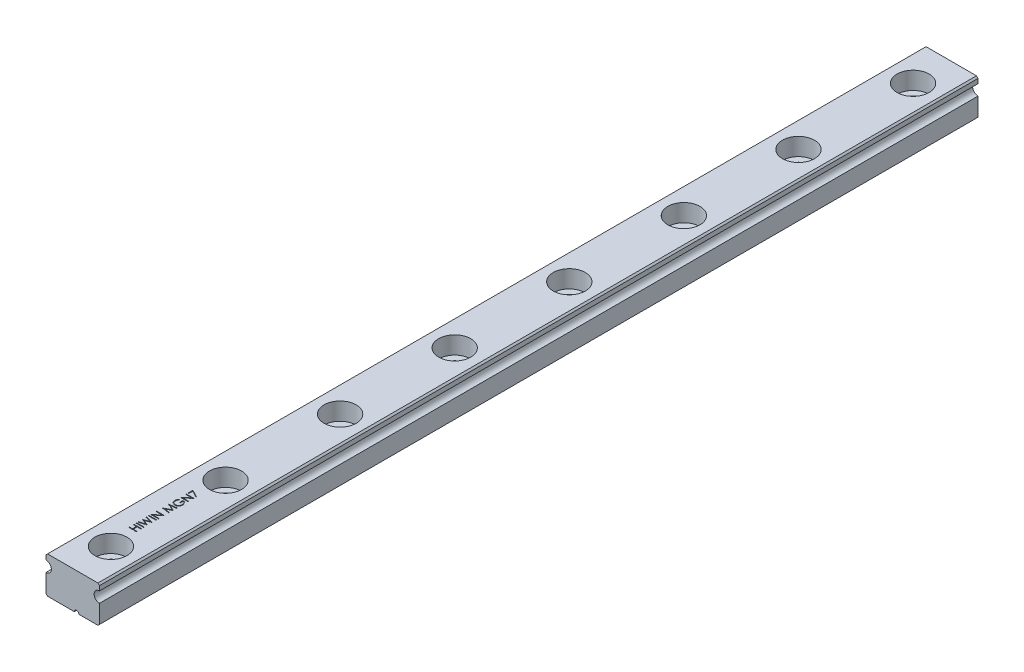
SolidWorks part; units mm, degrees
material "镀铬不锈钢"
ref_plane "前视基准面" through (0, 0, 0) normal (0, 0, 1) x (1, 0, 0)
ref_plane "上视基准面" through (0, 0, 0) normal (0, 1, 0) x (1, 0, 0)
ref_plane "右视基准面" through (0, 0, 0) normal (1, 0, 0) x (0, 0, -1)
sketch "草图1" plane through (0, 0, 0) normal (0, 0, 1) x (1, 0, 0)
  line L2 (-3.5, 4.6) -> (-3.5, 4)
  line L3 (0.8, 0) -> (3.3, 0)
  line L4 (-3.3, 0) -> (0.2, 0)
  line L5 (-3.5, 0.2) -> (-3.3, 0)
  line L6 (3.5, 0.2) -> (3.5, 2.6)
  line L7 (-3.3, 4.8) -> (-3.5, 4.6)
  line L8 (-3.5, 2.6) -> (-3.5, 0.2)
  line L9 (3.5, 4) -> (3.5, 4.6)
  line L10 (3.3, 0) -> (3.5, 0.2)
  line L11 (3.5, 4.6) -> (3.3, 4.8)
  line L12 (3.3, 4.8) -> (-3.3, 4.8)
  line L13 (0, 4.8) -> (0, 0) construction
  arc A0 (3.5, 4) -> (3.5, 2.6) centre (3.5, 3.3) ccw
  arc A1 (-3.5, 2.6) -> (-3.5, 4) centre (-3.5, 3.3) ccw
  arc A2 (0.8, 0) -> (0.2, 0) centre (0.5, 0) ccw
extrude "凸台-拉伸1" add sketch "草图1" against normal blind 115
hole_wizard "M2 六角凹头螺钉的柱形沉头孔1" positions "草图3" profile "草图2" counterbore size "M2" standard "ISO" end condition through all
sketch "草图3" plane through (1.648, 4.8, 19.9771) normal (0, 1, 0) x (-1, 0, 0)
  point P0 (1.648, -24.9771)
  dimension "D1" = 5
sketch "草图2" plane through (0, 4.8, -5) normal (1, 0, 0) x (0, 0, 1)
  line L0 (0, 0) -> (0, 4.8)
  line L1 (0, 4.8) -> (1.2, 4.8)
  line L3 (1.2, 4.8) -> (1.2, 2.3)
  line L4 (1.2, 2.3) -> (2.1, 2.3)
  line L5 (2.1, 2.3) -> (2.1, 0)
  line L7 (2.1, 0) -> (0, 0)
  line L11 (0, -6.35) -> (0, 107.95) construction
  dimension "通孔孔直径" = 2.4
  dimension "通孔孔深度" = 4.8
  dimension "柱形沉头孔直径" = 4.2
  dimension "柱形沉头孔深度" = 2.3
pattern_linear "阵列(线性)1" count 8 spacing 15 along (0, 0, -1) of "M2 六角凹头螺钉的柱形沉头孔1"
sketch "草图6" plane through (0, 4.8, 0) normal (0, 1, 0) x (1, 0, 0)
  line L0 (0, 5) -> (0, 20) construction
  text T0 "HIWIN MGN7" font "Century Gothic" height 1
extrude "切除-拉伸1" cut sketch "草图6" against normal blind 0.1
equation "\"D1@凸台-拉伸1\" = 2 * \"D1@草图3\" + \"D3@阵列(线性)1\" *  ( \"D1@阵列(线性)1\"  - 1) "
